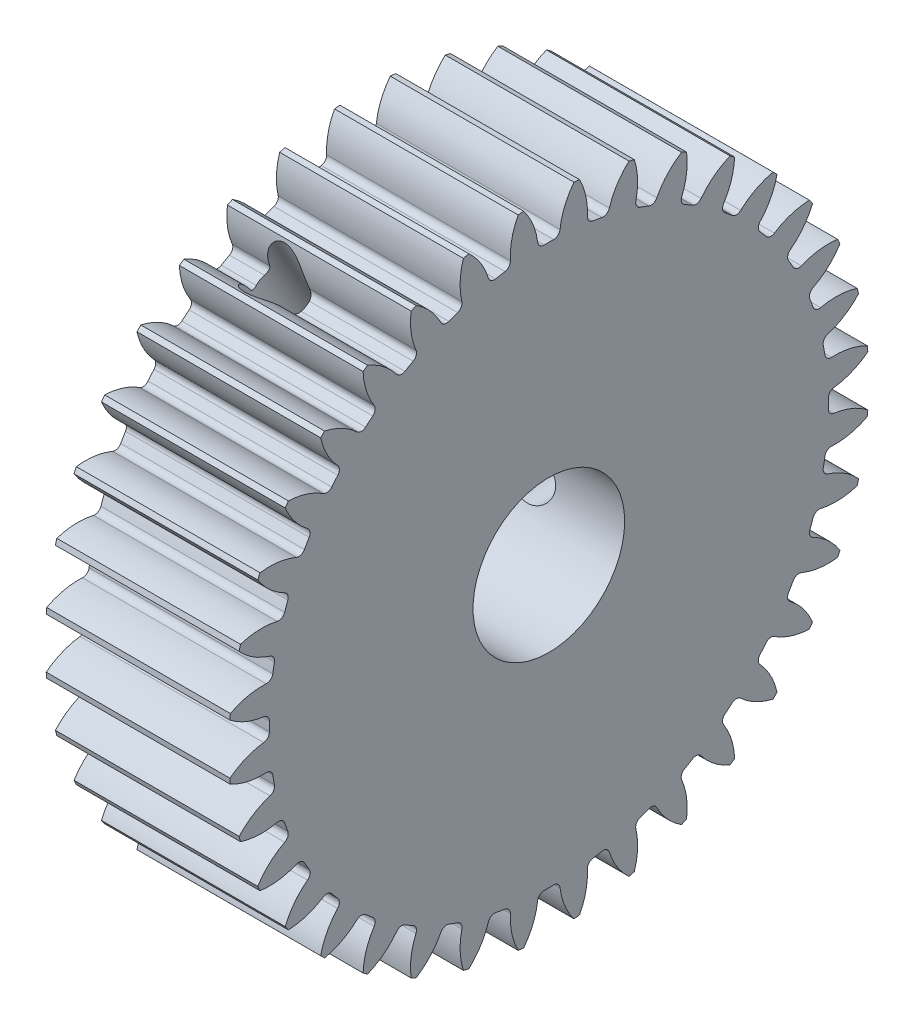
SolidWorks part; units mm, degrees
ref_plane "Front Plane" through (0, 0, 0) normal (0, 0, 1) x (1, 0, 0)
ref_plane "Top Plane" through (0, 0, 0) normal (0, 1, 0) x (1, 0, 0)
ref_plane "Right Plane" through (0, 0, 0) normal (1, 0, 0) x (0, 0, -1)
sketch "Sketch1" plane through (0, 0, 0) normal (1, 0, 0) x (0, 0, -1)
  circle A0 centre (0, 0) radius 4.953
  circle A1 centre (0, 0) radius 20.9
  dimension "D1" = 9.906
  dimension "D2" = 41.8
extrude "Boss-Extrude2" add sketch "Sketch1" along normal blind 12
sketch "Sketch3" plane through (12, 0, 0) normal (1, 0, 0) x (0, 0, -1)
  line L0 (0, 0) -> (0, 20.9) construction
  line L1 (-0.6995, 18.2466) -> (0, 0) construction
  line L2 (0, 16.9556) -> (-1.7175, 21.6745) construction
  circle A0 centre (0, 0) radius 20.9 construction
  arc A1 (0.6995, 18.2466) -> (-0.6995, 18.2466) centre (0, 0) ccw
  arc A2 (1.0289, 19.7732) -> (-1.0289, 19.7732) centre (0, 0) ccw construction
  arc A3 (1.6417, 20.8354) -> (-1.6417, 20.8354) centre (0, 0) ccw
  arc A4 (-1.6417, 20.8354) -> (-0.6995, 18.2466) centre (-5.2011, 18.074) cw
  arc A5 (1.6417, 20.8354) -> (0.6995, 18.2466) centre (5.2011, 18.074) ccw
  point P17 (-0.9679, 19.6148)
  dimension "D1" = 41.8
  dimension "D2" = 39.6
  dimension "D3" = 2.64
  dimension "D4" = 20
  dimension "D5" = 2.0579
extrude "Cut-Extrude1" cut sketch "Sketch3" against normal through all
fillet "Fillet1" radius 0.418 2 edges at (6, 18.2466, -0.6995) (6, 18.2466, 0.6995)
pattern_circular "CirPattern2" count 36 over 360 about axis through (0, 0, 0) along (1, 0, 0) of "Fillet1", "Cut-Extrude1"
ref_plane "Plane1" through (0, 0, -4.953) normal (0, 0, 1) x (1, 0, 0)
ref_plane "Plane2" through (0, 4.2894, 2.4765) normal (0, -0.866, -0.5) x (-1, 0, 0)
ref_plane "Plane3" through (0, -4.2894, 2.4765) normal (0, 0.866, -0.5) x (-1, 0, 0)
sketch "Sketch4" plane through (0, 0, -4.953) normal (0, 0, 1) x (1, 0, 0)
  line L0 (0, -0.308) -> (12, -0.308) construction
  circle A0 centre (6, -0.308) radius 1.5
  point P4 (3.75, -0.308)
  point P5 (3.75, -0.308)
  dimension "D1" = 3
sketch "Sketch5" plane through (0, 4.2894, 2.4765) normal (0, -0.866, -0.5) x (-1, 0, 0)
  circle A0 centre (-3.75, 0) radius 1.5
  point P2 (-1.4339, -0.7867)
  point P3 (0, 0)
  point P4 (0, 0)
  point P5 (0, 0)
  point P6 (-3.8775, 1.4616)
  point P7 (0, 0)
  point P8 (0, 0)
  point P9 (0, 0)
  point P10 (-2.8148, 3.549)
  point P11 (0, 0)
  point P13 (-4.4241, 0)
  point P15 (-3.75, 0)
  point P16 (-3.75, 0)
  point P17 (-3.75, 0)
  point P18 (0, 0)
  dimension "D1" = 3
sketch "Sketch6" plane through (0, -4.2894, 2.4765) normal (0, 0.866, -0.5) x (-1, 0, 0)
  circle A0 centre (-3.75, 0) radius 1.5
  point P2 (-3.3822, -1.4826)
  point P3 (-2.3613, -0.6127)
  point P4 (-3.75, -3.4737)
  point P5 (-3.75, -3.4737)
  point P6 (0, 0)
  point P7 (0, 0)
  point P9 (-3.75, 0)
  dimension "D1" = 3
extrude "Cut-Extrude2" cut sketch "Sketch4" against normal through all and the other way up to next
extrude "Cut-Extrude3" cut sketch "Sketch5" against normal through all and the other way up to next
extrude "Cut-Extrude4" cut sketch "Sketch6" against normal through all and the other way up to next
equation "\"No of teeth\"= 36"
equation "\"Module\"= 1.1"
equation "\"Outer Diameter\"= ( \"No of teeth\" + 2 ) * \"Module\""
equation "\"Pitch Diameter\"= \"No of teeth\" * \"Module\""
equation "\"Backlash\"= 0.3 * \"Module\""
equation "\"Arc Length\"= ( ( \"Module\" * pi ) / 2 ) + \"Backlash\""
equation "\"Fillet Radius\"= 0.38 * \"Module\""
equation "\"Bore Diameter\" = .39in"
equation "\"Presseure angle\"= 20"
equation "\"Tooth Depth\"= IIF ( \"Module\" <= 1.25 , 2.4 * \"Module\" , 2.25 * \"Module\" )"
equation "\"D1@Sketch1\"=\"Bore Diameter\""
equation "\"D2@Sketch1\"=\"Outer Diameter\""
equation "\"D1@Sketch3\"=\"Outer Diameter\""
equation "\"D2@Sketch3\"=\"Pitch Diameter\""
equation "\"D3@Sketch3\"=\"Tooth Depth\""
equation "\"D4@Sketch3\"=\"Presseure angle\""
equation "\"D5@Sketch3\"=\"Arc Length\""
equation "\"D1@Fillet1\"=\"Fillet Radius\""
equation "\"D1@CirPattern2\"=\"No of teeth\""
